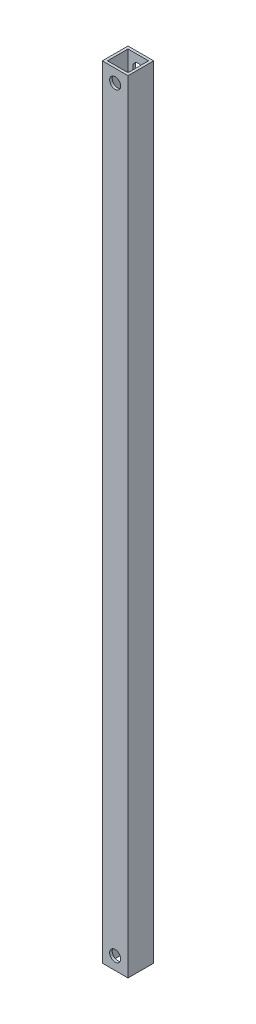
SolidWorks part; units mm, degrees
material "5052-H34"
ref_plane "正面" through (0, 0, 0) normal (0, 0, 1) x (1, 0, 0)
ref_plane "平面" through (0, 0, 0) normal (0, 1, 0) x (1, 0, 0)
ref_plane "右側面" through (0, 0, 0) normal (1, 0, 0) x (0, 0, -1)
sketch "ｽｹｯﾁ1" plane through (0, 0, 0) normal (0, 1, 0) x (1, 0, 0)
  line L1 (-5, 5) -> (5, 5)
  line L2 (-5, 5) -> (-5, -5)
  line L3 (-5, -5) -> (5, -5)
  line L4 (5, 5) -> (5, -5)
  line L5 (-5, 5) -> (5, -5) construction
  line L6 (-5, -5) -> (5, 5) construction
  point P0 (0, 0)
  dimension "D1" = 10
  dimension "D2" = 10
extrude "押し出し-薄板1" add sketch "ｽｹｯﾁ1" along normal blind 304.359 thin
sketch "ｽｹｯﾁ2" plane through (0, 0, 5) normal (0, 0, 1) x (1, 0, 0)
  line L0 (0, 304.359) -> (0, 299.359) construction
  line L1 (-5, 304.359) -> (5, 304.359) construction
  line L2 (-5, 152.1795) -> (5, 152.1795) construction
  line L3 (-5, 304.359) -> (-5, 0) construction
  line L4 (5, 304.359) -> (5, 0) construction
  circle A0 centre (0, 299.359) radius 2.15
  circle A1 centre (0, 5) radius 2.15
  dimension "D1" = 4.3
  dimension "D2" = 5
extrude "ｶｯﾄ - 押し出し1" cut sketch "ｽｹｯﾁ2" against normal through all
equation "\"D1@押し出し-薄板1\"=sqr(125^2+266.5^2)+10"
